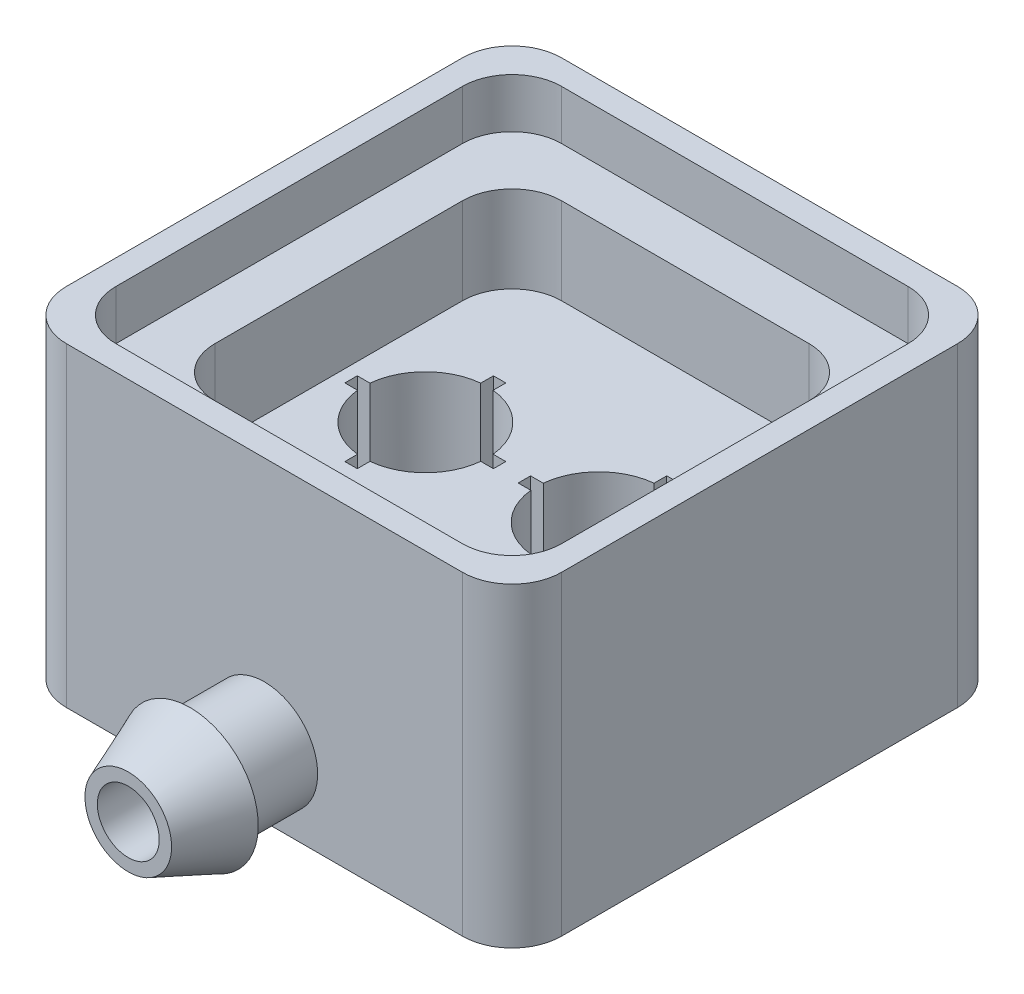
SolidWorks part; units mm, degrees
ref_plane "Front Plane" through (0, 0, 0) normal (0, 0, 1) x (1, 0, 0)
ref_plane "Top Plane" through (0, 0, 0) normal (0, 1, 0) x (1, 0, 0)
ref_plane "Right Plane" through (0, 0, 0) normal (1, 0, 0) x (0, 0, -1)
sketch "Sketch1" plane through (0, 0, 0) normal (0, 1, 0) x (1, 0, 0)
  line L0 (-3.5, 0) -> (3.5, 0) construction
  line L1 (-8, -10) -> (8, -10)
  line L2 (-10, -8) -> (-10, 8)
  line L3 (-8, 10) -> (8, 10)
  line L4 (10, -8) -> (10, 8)
  line L5 (-10, -10) -> (10, 10) construction
  line L6 (-10, 10) -> (10, -10) construction
  arc A0 (-10, 8) -> (-8, 10) centre (-8, 8) cw
  arc A1 (8, 10) -> (10, 8) centre (8, 8) cw
  arc A2 (-10, -8) -> (-8, -10) centre (-8, -8) ccw
  arc A3 (10, -8) -> (8, -10) centre (8, -8) cw
  circle A4 centre (3.5, 0) radius 2.5
  circle A5 centre (-3.5, 0) radius 2.5
  point P0 (0, 0)
  point P21 (0, 0)
  dimension "D3" = 2
  dimension "D4" = 2
  dimension "D6" = 5
  dimension "D7" = 5
  dimension "D1" = 20
  dimension "D2" = 20
  dimension "D5" = 7
extrude "Boss-Extrude1" add sketch "Sketch1" along normal blind 7.23
sketch "Sketch2" plane through (0, 7.23, 0) normal (0, 1, 0) x (1, 0, 0)
  line L0 (-3.5, 0) -> (3.5, 0) construction
  line L2 (-6.5, -0.25) -> (-0.5, -0.25)
  line L3 (-6.5, -0.25) -> (-6.5, 0.25)
  line L4 (-6.5, 0.25) -> (-0.5, 0.25)
  line L5 (-0.5, -0.25) -> (-0.5, 0.25)
  line L6 (-6.5, -0.25) -> (-0.5, 0.25) construction
  line L7 (-6.5, 0.25) -> (-0.5, -0.25) construction
  line L8 (-3.75, -3) -> (-3.25, -3)
  line L9 (-3.75, -3) -> (-3.75, 3)
  line L10 (-3.75, 3) -> (-3.25, 3)
  line L11 (-3.25, -3) -> (-3.25, 3)
  line L12 (-3.75, -3) -> (-3.25, 3) construction
  line L13 (-3.75, 3) -> (-3.25, -3) construction
  line L14 (3.25, -3) -> (3.75, -3)
  line L15 (3.25, -3) -> (3.25, 3)
  line L16 (3.25, 3) -> (3.75, 3)
  line L17 (3.75, -3) -> (3.75, 3)
  line L18 (3.25, -3) -> (3.75, 3) construction
  line L19 (3.25, 3) -> (3.75, -3) construction
  line L20 (0.5, -0.25) -> (6.5, -0.25)
  line L21 (0.5, -0.25) -> (0.5, 0.25)
  line L22 (0.5, 0.25) -> (6.5, 0.25)
  line L23 (6.5, -0.25) -> (6.5, 0.25)
  line L24 (0.5, -0.25) -> (6.5, 0.25) construction
  line L25 (0.5, 0.25) -> (6.5, -0.25) construction
  point P3 (0, 0)
  circle M15 centre (3.5, 0) radius 2.5
  circle M16 centre (-3.5, 0) radius 2.5
  dimension "D1" = 7
  dimension "D2" = 6
  dimension "D3" = 6
  dimension "D4" = 6
  dimension "D5" = 6
  dimension "D6" = 0.5
  dimension "D7" = 0.5
  dimension "D8" = 0.5
  dimension "D9" = 0.5
extrude "Cut-Extrude1" cut sketch "Sketch2" against normal blind 6.43 contours L17 L16 L15 M15 | L20 L23 L22 M15 | L14 L17 L15 M15 | L22 L21 L20 M15 | L2 L5 L4 M16 | L11 L10 L9 M16 | L4 L3 L2 M16 | L8 L11 L9 M16
sketch "Sketch3" plane through (0, 0, 0) normal (1, 0, 0) x (0, 0, -1)
  line L0 (-10, 0.6) -> (-13, 0.6)
  line L1 (-10, 7.23) -> (-10, 0) construction
  line L2 (-13, 0.6) -> (-13, 0)
  line L3 (-13, 0) -> (-15.5, 1)
  line L4 (-15.5, 1) -> (-15.5, 1.5)
  line L5 (-15.5, 1.5) -> (-10, 1.5)
  line L6 (-10, 1.5) -> (-10, 0.6)
  line L7 (-10, 2.75) -> (-13.6025, 2.75) construction
  line L8 (-8, 0) -> (8, 0) construction
  point P10 (0, 0)
  dimension "D1" = 2.5
  dimension "D2" = 3
  dimension "D3" = 1.75
  dimension "D4" = 2.15
  dimension "D5" = 1.25
  dimension "D6" = 2.75
revolve "Revolve1" add sketch "Sketch3" angle 360 about L7
sketch "Sketch5" plane through (0, 0, 10) normal (0, 0, 1) x (1, 0, 0)
  circle A0 centre (0, 2.75) radius 1.25
extrude "Cut-Extrude2" cut sketch "Sketch5" against normal blind 13
sketch "Sketch6" plane through (0, 7.23, 0) normal (0, 1, 0) x (1, 0, 0)
  line L1 (-8, -10) -> (8, -10)
  line L2 (-10, -8) -> (-10, 8)
  line L3 (-8, 10) -> (8, 10)
  line L4 (10, -8) -> (10, 8)
  line L5 (-10, -10) -> (10, 10) construction
  line L6 (-10, 10) -> (10, -10) construction
  line L7 (-5, -7) -> (5, -7)
  line L8 (-7, -5) -> (-7, 5)
  line L9 (-5, 7) -> (5, 7)
  line L10 (7, -5) -> (7, 5)
  line L11 (-7, -7) -> (7, 7) construction
  line L12 (-7, 7) -> (7, -7) construction
  arc A0 (-10, -8) -> (-8, -10) centre (-8, -8) ccw
  arc A1 (10, -8) -> (8, -10) centre (8, -8) cw
  arc A2 (10, 8) -> (8, 10) centre (8, 8) ccw
  arc A3 (-8, 10) -> (-10, 8) centre (-8, 8) ccw
  arc A4 (-7, -5) -> (-5, -7) centre (-5, -5) ccw
  arc A5 (5, -7) -> (7, -5) centre (5, -5) ccw
  arc A6 (7, 5) -> (5, 7) centre (5, 5) ccw
  arc A7 (-5, 7) -> (-7, 5) centre (-5, 5) ccw
  point P0 (0, 0)
  point P18 (0, 0)
  dimension "D3" = 2
  dimension "D1" = 20
  dimension "D2" = 20
  dimension "D6" = 2
  dimension "D4" = 3
  dimension "D5" = 3
extrude "Boss-Extrude2" add sketch "Sketch6" along normal blind 3.5
sketch "Sketch8" plane through (0, 10.73, 0) normal (0, 1, 0) x (1, 0, 0)
  line L1 (-8, -10) -> (8, -10)
  line L2 (-10, -8) -> (-10, 8)
  line L3 (-8, 10) -> (8, 10)
  line L4 (10, -8) -> (10, 8)
  line L5 (-10, -10) -> (10, 10) construction
  line L6 (-10, 10) -> (10, -10) construction
  line L7 (-7, -9) -> (7, -9)
  line L8 (-9, -7) -> (-9, 7)
  line L9 (-7, 9) -> (7, 9)
  line L10 (9, -7) -> (9, 7)
  line L11 (-9, -9) -> (9, 9) construction
  line L12 (-9, 9) -> (9, -9) construction
  arc A0 (10, 8) -> (8, 10) centre (8, 8) ccw
  arc A1 (10, -8) -> (8, -10) centre (8, -8) cw
  arc A2 (-10, -8) -> (-8, -10) centre (-8, -8) ccw
  arc A3 (-10, 8) -> (-8, 10) centre (-8, 8) cw
  arc A4 (-9, -7) -> (-7, -9) centre (-7, -7) ccw
  arc A5 (7, -9) -> (9, -7) centre (7, -7) ccw
  arc A6 (9, 7) -> (7, 9) centre (7, 7) ccw
  arc A7 (-9, 7) -> (-7, 9) centre (-7, 7) cw
  point P0 (0, 0)
  point P18 (0, 0)
  dimension "D3" = 2
  dimension "D1" = 20
  dimension "D2" = 20
  dimension "D6" = 2
  dimension "D4" = 1
  dimension "D5" = 1
extrude "Boss-Extrude3" add sketch "Sketch8" along normal blind 2
equation "\"D2@Sketch1\"=\"D1@Sketch1\""
equation "\"D7@Sketch1\"=\"D6@Sketch1\""
equation "\"D3@Sketch2\"=\"D2@Sketch2\""
equation "\"D2@Sketch2\"=\"D6@Sketch1\"+1mm"
equation "\"D4@Sketch2\"=\"D2@Sketch2\""
equation "\"D5@Sketch2\"=\"D2@Sketch2\""
equation "\"D7@Sketch2\"=\"D6@Sketch2\""
equation "\"D8@Sketch2\"=\"D6@Sketch2\""
equation "\"D9@Sketch2\"=\"D6@Sketch2\""
equation "\"D1@Sketch6\"=\"D1@Sketch1\""
equation "\"D2@Sketch6\"=\"D1@Sketch1\""
equation "\"D5@Sketch6\"=\"D4@Sketch6\""
equation "\"D1@Sketch8\"=\"D1@Sketch1\""
equation "\"D2@Sketch8\"=\"D1@Sketch1\""
